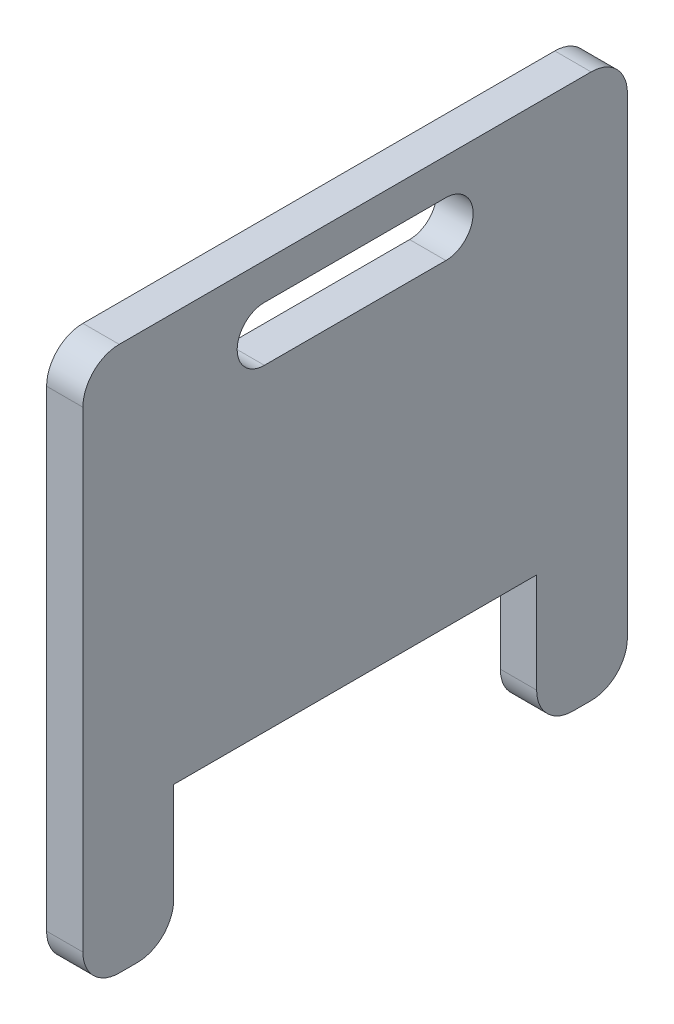
SolidWorks part; units mm, degrees
ref_plane "Front Plane" through (0, 0, 0) normal (0, 0, 1) x (1, 0, 0)
ref_plane "Top Plane" through (0, 0, 0) normal (0, 1, 0) x (1, 0, 0)
ref_plane "Right Plane" through (0, 0, 0) normal (1, 0, 0) x (0, 0, -1)
sketch "Sketch10" plane through (0, 0, 0) normal (1, 0, 0) x (0, 0, -1)
  line L1 (150, 187.5) -> (0, 187.5)
  line L2 (150, 187.5) -> (150, 37.5)
  line L3 (150, 37.5) -> (0, 37.5)
  line L4 (0, 187.5) -> (0, 37.5)
  line L5 (150, 187.5) -> (0, 37.5) construction
  line L6 (150, 37.5) -> (0, 187.5) construction
  point P0 (75, 112.5)
  dimension "D1" = 150
  dimension "D2" = 150
extrude "Boss-Extrude3" add sketch "Sketch10" along normal blind 10
sketch "Sketch12" plane through (0, 0, 0) normal (-1, 0, 0) x (0, 0, 1)
  line L0 (0, 37.5) -> (-150, 37.5) construction
  line L1 (-125, 37.5) -> (-25, 37.5)
  line L2 (-125, 37.5) -> (-125, 75)
  line L3 (-125, 75) -> (-25, 75)
  line L4 (-25, 37.5) -> (-25, 75)
  dimension "D1" = 25
  dimension "D2" = 25
extrude "Cut-Extrude2" cut sketch "Sketch12" against normal blind 10
fillet "Fillet7" radius 10 6 edges at (5, 37.5, -150) (5, 37.5, -125) (5, 37.5, -25) (5, 37.5, 0) (5, 187.5, -150) (5, 187.5, 0)
sketch "Sketch13" plane through (10, 0, 0) normal (1, 0, 0) x (0, 0, -1)
  line L0 (75, 50) -> (75, 225) construction
  line L1 (50, 170) -> (100, 170) construction
  line L2 (50, 177.5) -> (100, 177.5)
  line L3 (50, 162.5) -> (100, 162.5)
  line L4 (140, 187.5) -> (10, 187.5) construction
  arc A0 (50, 177.5) -> (50, 162.5) centre (50, 170) ccw
  arc A1 (100, 162.5) -> (100, 177.5) centre (100, 170) ccw
  point P4 (75, 170)
  point P11 (0, 0)
  point P12 (0, 0)
  point P13 (0, 0)
  dimension "D1" = 15
  dimension "D2" = 50
  dimension "D3" = 10
extrude "Cut-Extrude3" cut sketch "Sketch13" against normal blind 35
